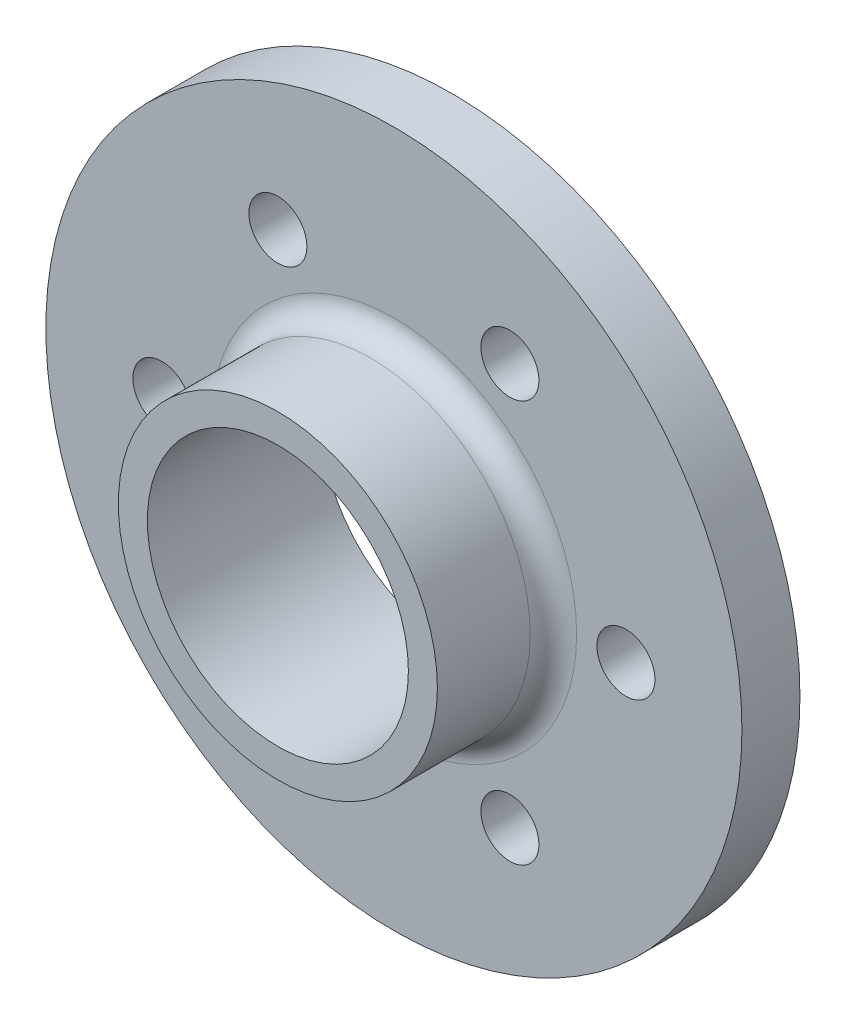
SolidWorks part; units mm, degrees
ref_plane "Front Plane" through (0, 0, 0) normal (0, 0, 1) x (1, 0, 0)
ref_plane "Top Plane" through (0, 0, 0) normal (0, 1, 0) x (1, 0, 0)
ref_plane "Right Plane" through (0, 0, 0) normal (1, 0, 0) x (0, 0, -1)
sketch "Sketch1" plane through (0, 0, 0) normal (0, 0, 1) x (1, 0, 0)
  line L0 (0, 0) -> (-25.4, 0) construction
  circle A0 centre (0, 0) radius 38.1
  circle A1 centre (0, 0) radius 25.4 construction
  point P18 (0, 0)
  dimension "D1" = 50.8
  dimension "D4" = 76.2
extrude "Boss-Extrude1" add sketch "Sketch1" along normal blind 6.35
sketch "Sketch2" plane through (0, 0, 6.35) normal (0, 0, 1) x (1, 0, 0)
  circle A0 centre (0, 0) radius 17.4625
  dimension "D1" = 34.925
extrude "Boss-Extrude2" add sketch "Sketch2" along normal blind 12.7
fillet "Fillet2" radius 2.54 1 edges at (17.4625, 0, 6.35)
sketch "Sketch3" plane through (0, 0, 19.05) normal (0, 0, 1) x (1, 0, 0)
  circle A0 centre (0, 0) radius 14.2875
  dimension "D1" = 28.575
extrude "Cut-Extrude1" cut sketch "Sketch3" against normal up to next contours A0
sketch "Sketch4" plane through (0, 0, 0) normal (0, 0, -1) x (-1, 0, 0)
  circle A0 centre (0, 0) radius 25.4 construction
  circle A1 centre (-25.4, 0) radius 3.175
  circle A2 centre (0, 0) radius 25.4 construction
  circle A3 centre (-12.7, 21.997) radius 3.175
  circle A4 centre (0, 0) radius 25.4 construction
  circle A5 centre (12.7, 21.997) radius 3.175
  circle A6 centre (0, 0) radius 25.4 construction
  circle A7 centre (25.4, 0) radius 3.175
  circle A8 centre (0, 0) radius 25.4 construction
  circle A9 centre (12.7, -21.997) radius 3.175
  circle A10 centre (0, 0) radius 25.4 construction
  circle A11 centre (-12.7, -21.997) radius 3.175
  point P23 (0, 0)
  dimension "D1" = 50.8
  dimension "D2" = 6.35
  dimension "D3" = 6
extrude "Cut-Extrude2" cut sketch "Sketch4" against normal through all
